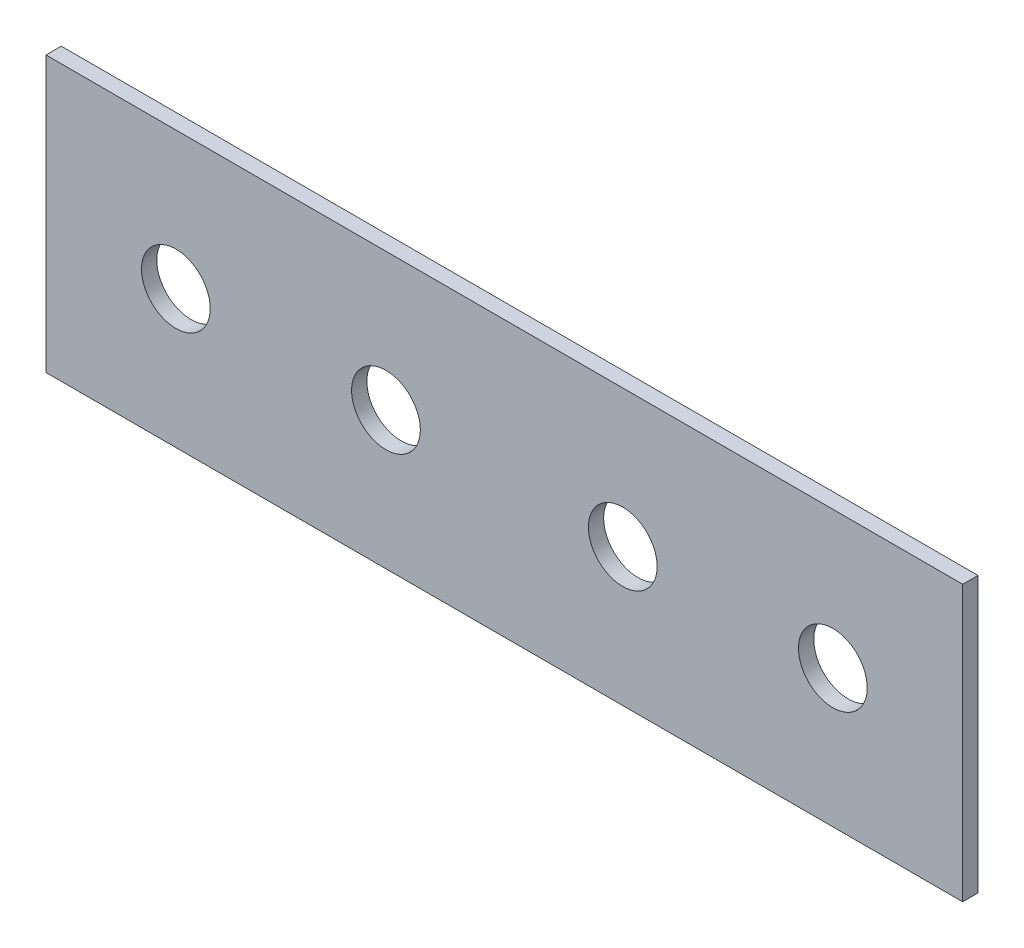
SolidWorks part; units mm, degrees
ref_plane "前视基准面" through (0, 0, 0) normal (0, 0, 1) x (1, 0, 0)
ref_plane "上视基准面" through (0, 0, 0) normal (0, 1, 0) x (1, 0, 0)
ref_plane "右视基准面" through (0, 0, 0) normal (1, 0, 0) x (0, 0, -1)
sketch "草图1" plane through (0, 0, 0) normal (0, 0, 1) x (1, 0, 0)
  line B0 (0, 0) -> (0, 36)
  line B1 (120, 36) -> (120, 0)
  line B2 (0, 0) -> (120, 0)
  line B3 (0, 36) -> (120, 36)
  circle B4 centre (17, 18) radius 4.5
  circle B5 centre (44.5, 18) radius 4.5
  circle B6 centre (75.5, 18) radius 4.5
  circle B7 centre (103, 18) radius 4.5
sketch_block_instance "A$C3ACA6E0E-1"
sketch_block "A$C3ACA6E0E"
extrude "凸台-拉伸1" add sketch "草图1" along normal blind 2
